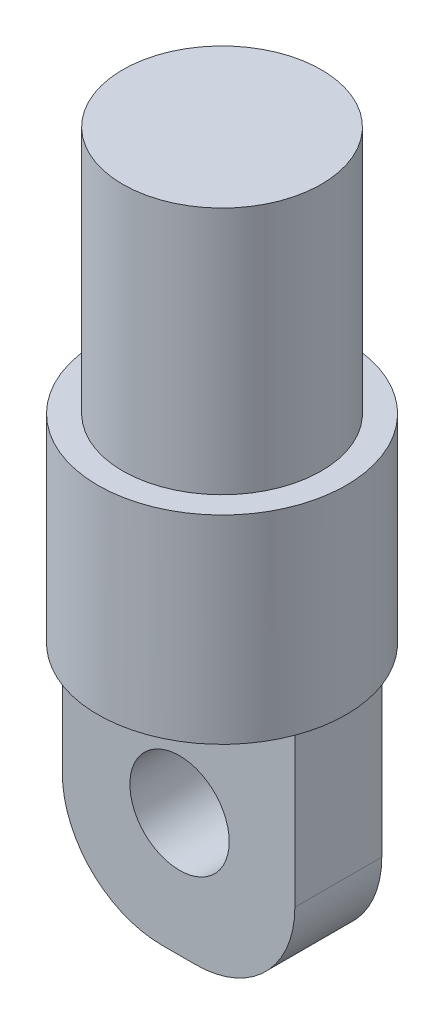
SolidWorks part; units mm, degrees
ref_plane "Front Plane" through (0, 0, 0) normal (0, 0, 1) x (1, 0, 0)
ref_plane "Top Plane" through (0, 0, 0) normal (0, 1, 0) x (1, 0, 0)
ref_plane "Right Plane" through (0, 0, 0) normal (1, 0, 0) x (0, 0, -1)
sketch "Sketch1" plane through (0, 0, 0) normal (0, 1, 0) x (1, 0, 0)
  circle A0 centre (0, 0) radius 31.75
  dimension "D1" = 63.5
extrude "Boss-Extrude1" add sketch "Sketch1" along normal blind 50.8
sketch "Sketch2" plane through (0, 50.8, 0) normal (0, 1, 0) x (1, 0, 0)
  circle A0 centre (0, 0) radius 25.4
extrude "Boss-Extrude2" add sketch "Sketch2" along normal blind 63.5
sketch "Sketch3" plane through (0, 0, 0) normal (0, -1, 0) x (1, 0, 0)
  line L1 (-29.7404, -11.1163) -> (29.7404, -11.1163)
  line L2 (-29.7404, -11.1163) -> (-29.7404, 11.1163)
  line L3 (-29.7404, 11.1163) -> (29.7404, 11.1163)
  line L4 (29.7404, -11.1163) -> (29.7404, 11.1163)
  line L5 (-29.7404, -11.1163) -> (29.7404, 11.1163) construction
  line L6 (-29.7404, 11.1163) -> (29.7404, -11.1163) construction
  circle A0 centre (0, 0) radius 31.75 construction
  point P0 (0, 0)
extrude "Boss-Extrude3" add sketch "Sketch3" along normal blind 63.5
sketch "Sketch4" plane through (0, 0, 11.1163) normal (0, 0, 1) x (1, 0, 0)
  circle A0 centre (0.244, -31.9671) radius 12.7
extrude "Cut-Extrude1" cut sketch "Sketch4" against normal through all contours A0
fillet "Fillet1" radius 25.4 1 edges at (-29.7404, -63.5, 0)
fillet "Fillet2" radius 25.4 1 edges at (29.7404, -63.5, 0)
